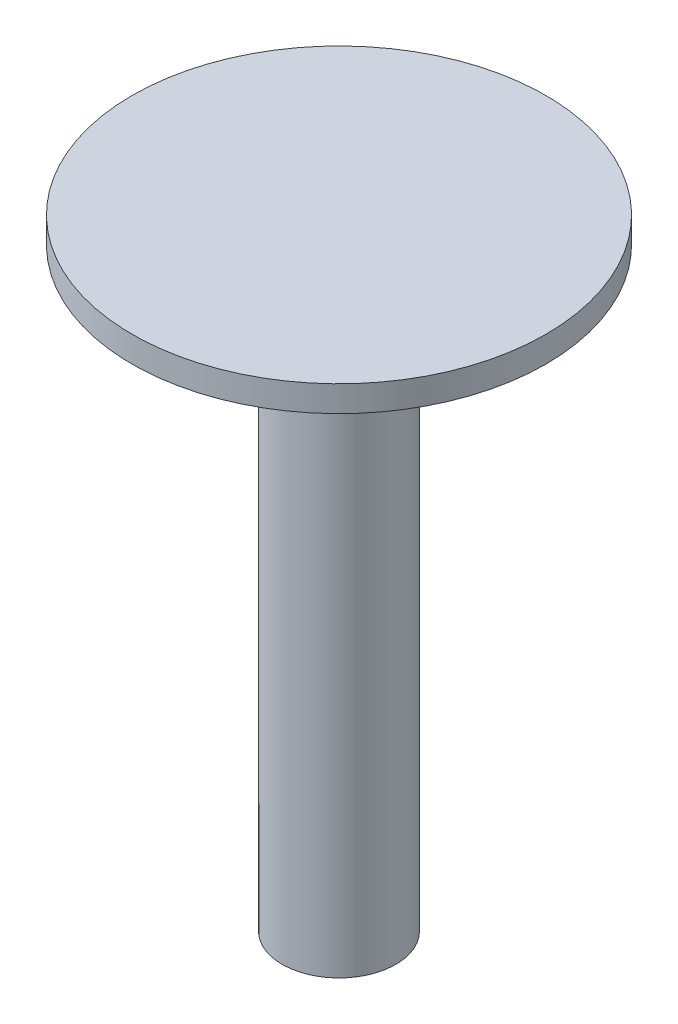
SolidWorks part; units mm, degrees
ref_plane "Front Plane" through (0, 0, 0) normal (0, 0, 1) x (1, 0, 0)
ref_plane "Top Plane" through (0, 0, 0) normal (0, 1, 0) x (1, 0, 0)
ref_plane "Right Plane" through (0, 0, 0) normal (1, 0, 0) x (0, 0, -1)
sketch "Sketch3" plane through (0, 0, 0) normal (0, 0, 1) x (1, 0, 0)
  line L0 (0, 120) -> (0, 0)
  line L1 (0, 120) -> (40, 120)
  line L2 (40, 120) -> (40, 115)
  line L3 (40, 115) -> (11, 115)
  line L4 (11, 115) -> (11, 0)
  line L5 (11, 0) -> (0, 0)
  dimension "D1" = 120
  dimension "D2" = 11
  dimension "D3" = 5
  dimension "D4" = 40
revolve "Revolve1" add sketch "Sketch3" angle 360 about L0
fillet "Fillet1" radius 2 1 edges at (-11, 115, 0)
